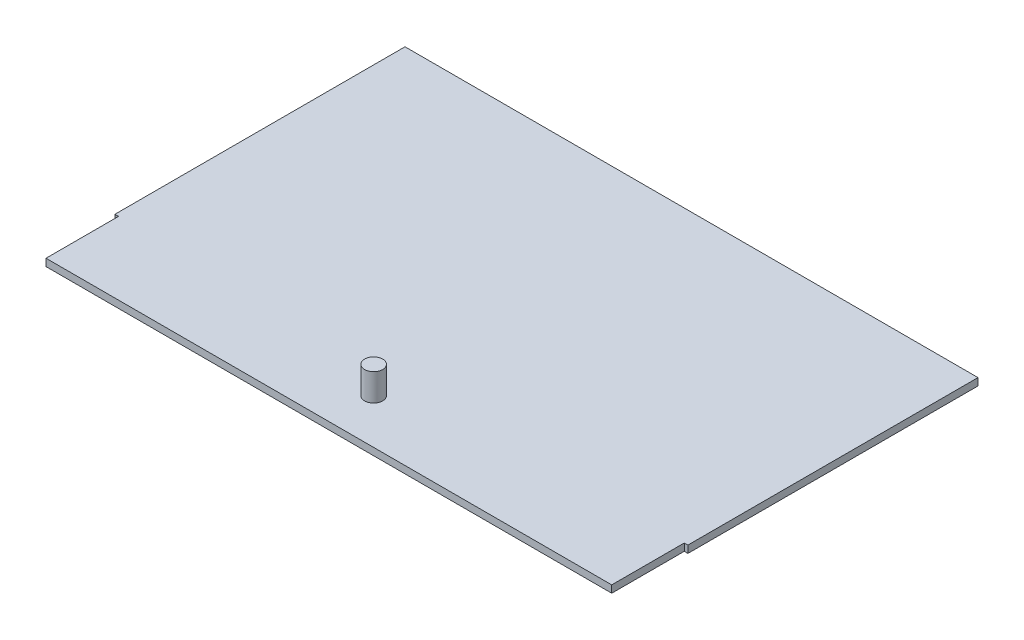
SolidWorks part; units mm, degrees
ref_plane "Front Plane" through (0, 0, 0) normal (0, 0, 1) x (1, 0, 0)
ref_plane "Top Plane" through (0, 0, 0) normal (0, 1, 0) x (1, 0, 0)
ref_plane "Right Plane" through (0, 0, 0) normal (1, 0, 0) x (0, 0, -1)
sketch "Sketch1" plane through (0, 0, 0) normal (0, 1, 0) x (1, 0, 0)
  line L0 (-5.476, 107.7101) -> (-5.476, 27.7101)
  line L1 (-5.476, 107.7101) -> (152.524, 107.7101)
  line L3 (-4.476, 7.7101) -> (151.524, 7.7101)
  line L4 (152.524, 107.7101) -> (152.524, 27.7101)
  line L5 (-5.476, 27.7101) -> (-4.476, 27.7101)
  line L6 (-4.476, 27.7101) -> (-4.476, 7.7101)
  line L8 (152.524, 27.7101) -> (151.524, 27.7101)
  line L9 (151.524, 27.7101) -> (151.524, 7.7101)
  dimension "D1" = 158
  dimension "D2" = 80
  dimension "D3" = 80
  dimension "D4" = 1
  dimension "D5" = 1
  dimension "D6" = 20
extrude "Boss-Extrude1" add sketch "Sketch1" along normal blind 2
sketch "Sketch2" plane through (0, 2, 0) normal (0, 1, 0) x (1, 0, 0)
  line L0 (73.524, 7.7101) -> (73.524, 20.0583) construction
  line L1 (-4.476, 7.7101) -> (151.524, 7.7101) construction
  circle A0 centre (73.524, 20.0583) radius 2.5
  dimension "D1" = 5
extrude "Boss-Extrude2" add sketch "Sketch2" along normal blind 7.5
